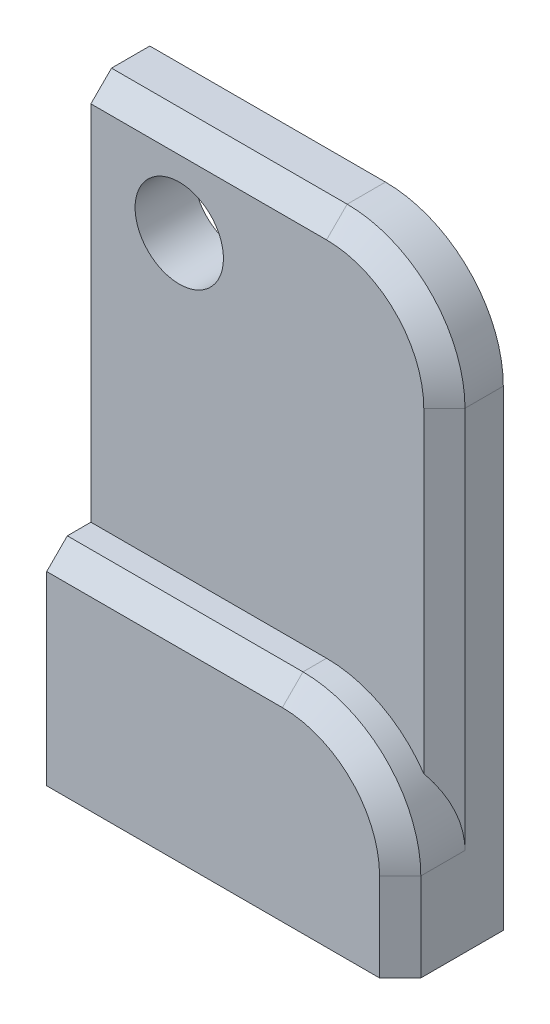
SolidWorks part; units mm, degrees
ref_plane "Front Plane" through (0, 0, 0) normal (0, 0, 1) x (1, 0, 0)
ref_plane "Top Plane" through (0, 0, 0) normal (0, 1, 0) x (1, 0, 0)
ref_plane "Right Plane" through (0, 0, 0) normal (1, 0, 0) x (0, 0, -1)
sketch "Sketch1" plane through (0, 0, 0) normal (0, 0, 1) x (1, 0, 0)
  line L1 (-60, -100) -> (60, -100)
  line L2 (-60, -100) -> (-60, 100)
  line L3 (-60, 100) -> (60, 100)
  line L4 (60, -100) -> (60, 100)
  line L5 (-60, -100) -> (60, 100) construction
  line L6 (-60, 100) -> (60, -100) construction
  point P0 (0, 0)
  dimension "D1" = 120
  dimension "D2" = 200
extrude "Boss-Extrude1" add sketch "Sketch1" along normal blind 20
sketch "Sketch2" plane through (0, 0, 20) normal (0, 0, 1) x (1, 0, 0)
  line L0 (60, -100) -> (60, 100) construction
  line L1 (-60, -100) -> (60, -100)
  line L2 (-60, -100) -> (-60, -30)
  line L3 (-60, -30) -> (60, -30)
  line L4 (60, -100) -> (60, -30)
  dimension "D1" = 70
extrude "Boss-Extrude2" add sketch "Sketch2" along normal blind 15
sketch "Sketch3" plane through (0, 0, 20) normal (0, 0, 1) x (1, 0, 0)
  line L0 (-60, 100) -> (-60, -30) construction
  line L1 (60, 100) -> (-60, 100) construction
  circle A0 centre (-30, 70) radius 15
  point P2 (0, 0)
  dimension "D1" = 30
  dimension "D2" = 30
  dimension "D3" = 30
extrude "Cut-Extrude1" cut sketch "Sketch3" against normal through all
fillet "Fillet1" radius 40 2 edges at (60, -30, 27.5) (60, 100, 10)
chamfer "Chamfer1" distance 7 angle 45 6 edges at (60, -85, 35) (48.2843, -41.7157, 35) (-20, -30, 35) (60, -5, 20) (48.2843, 88.2843, 20) (-20, 100, 20)
shell "Shell2" thickness 5
